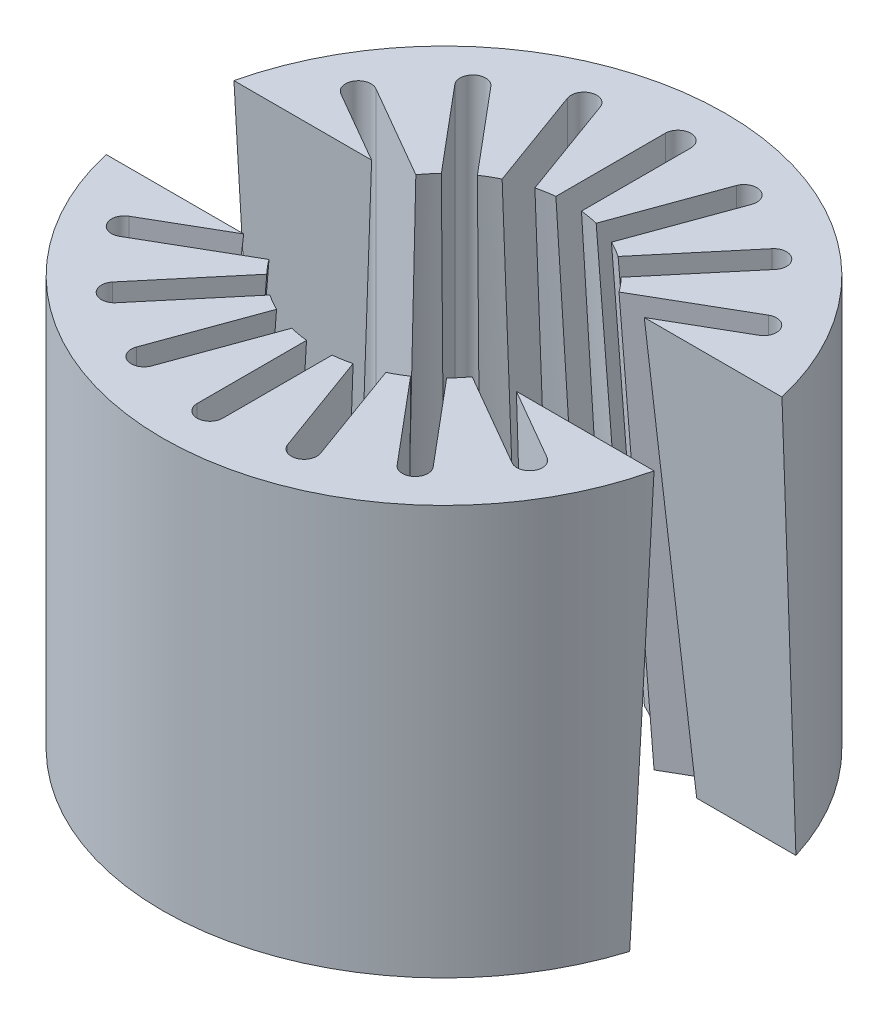
SolidWorks part; units mm, degrees
ref_plane "Front Plane" through (0, 0, 0) normal (0, 0, 1) x (1, 0, 0)
ref_plane "Top Plane" through (0, 0, 0) normal (0, 1, 0) x (1, 0, 0)
ref_plane "Right Plane" through (0, 0, 0) normal (1, 0, 0) x (0, 0, -1)
sketch "Sketch1" plane through (0, 0, 0) normal (0, 1, 0) x (1, 0, 0)
  line L1 (11, -7.5) -> (-11, -7.5) construction
  line L2 (11, -7.5) -> (11, 7.5) construction
  line L3 (11, 7.5) -> (-11, 7.5) construction
  line L4 (-11, -7.5) -> (-11, 7.5) construction
  line L5 (11, -7.5) -> (-11, 7.5) construction
  line L6 (11, 7.5) -> (-11, -7.5) construction
  circle A0 centre (0, 0) radius 5 construction
  circle A1 centre (0, 0) radius 11
  point P0 (0, 0)
  dimension "D1" = 10
  dimension "D2" = 22
  dimension "D3" = 15
extrude "Boss-Extrude1" add sketch "Sketch1" along normal blind 16
sketch "Sketch2" plane through (0, 0, 0) normal (1, 0, 0) x (0, 0, -1)
  line L0 (0, 0) -> (0, 16)
  line L2 (0, 16) -> (4.9, 16)
  line L3 (4.9, 16) -> (5.9, 0)
  line L5 (5.9, 0) -> (0, 0)
  line L6 (11, 16) -> (-11, 16) construction
  line L7 (-11, 0) -> (11, 0) construction
  dimension "D1" = 4.9
  dimension "5.9" = 5.9
revolve "Cut-Revolve1" cut sketch "Sketch2" angle 360 about L0
sketch "Sketch3" plane through (0, 16, 0) normal (0, 1, 0) x (1, 0, 0)
  line L0 (0, 4.8) -> (0, 0) construction
  line L1 (-0.5, 4.8) -> (0.5, 4.8)
  line L2 (-0.5, 4.8) -> (-0.5, 9.15)
  line L4 (0.5, 4.8) -> (0.5, 9.15)
  line L5 (1.1719, 4.6815) -> (2.1115, 4.3395)
  line L6 (1.1719, 4.6815) -> (2.6596, 8.7692)
  line L7 (2.1115, 4.3395) -> (3.5993, 8.4272)
  line L8 (2.7024, 3.9984) -> (3.4684, 3.3556)
  line L9 (2.7024, 3.9984) -> (5.4985, 7.3307)
  line L10 (3.4684, 3.3556) -> (6.2645, 6.6879)
  line L11 (3.9069, 2.833) -> (4.4069, 1.967)
  line L12 (3.9069, 2.833) -> (7.6741, 5.008)
  line L13 (4.4069, 1.967) -> (8.1741, 4.142)
  line L14 (4.6403, 1.3259) -> (4.8139, 0.3411)
  line L15 (4.6403, 1.3259) -> (8.9242, 2.0813)
  line L16 (4.8139, 0.3411) -> (9.0978, 1.0965)
  line L17 (4.8139, -0.3411) -> (4.6403, -1.3259)
  line L18 (4.8139, -0.3411) -> (9.0978, -1.0965)
  line L19 (4.6403, -1.3259) -> (8.9242, -2.0813)
  line L20 (4.4069, -1.967) -> (3.9069, -2.833)
  line L21 (4.4069, -1.967) -> (8.1741, -4.142)
  line L22 (3.9069, -2.833) -> (7.6741, -5.008)
  line L23 (3.4684, -3.3556) -> (2.7024, -3.9984)
  line L24 (3.4684, -3.3556) -> (6.2645, -6.6879)
  line L25 (2.7024, -3.9984) -> (5.4985, -7.3307)
  line L26 (2.1115, -4.3395) -> (1.1719, -4.6815)
  line L27 (2.1115, -4.3395) -> (3.5993, -8.4272)
  line L28 (1.1719, -4.6815) -> (2.6596, -8.7692)
  line L29 (0.5, -4.8) -> (-0.5, -4.8)
  line L30 (0.5, -4.8) -> (0.5, -9.15)
  line L31 (-0.5, -4.8) -> (-0.5, -9.15)
  line L32 (-1.1719, -4.6815) -> (-2.1115, -4.3395)
  line L33 (-1.1719, -4.6815) -> (-2.6596, -8.7692)
  line L34 (-2.1115, -4.3395) -> (-3.5993, -8.4272)
  line L35 (-2.7024, -3.9984) -> (-3.4684, -3.3556)
  line L36 (-2.7024, -3.9984) -> (-5.4985, -7.3307)
  line L37 (-3.4684, -3.3556) -> (-6.2645, -6.6879)
  line L38 (-3.9069, -2.833) -> (-4.4069, -1.967)
  line L39 (-3.9069, -2.833) -> (-7.6741, -5.008)
  line L40 (-4.4069, -1.967) -> (-8.1741, -4.142)
  line L41 (-4.6403, -1.3259) -> (-4.8139, -0.3411)
  line L42 (-4.6403, -1.3259) -> (-8.9242, -2.0813)
  line L43 (-4.8139, -0.3411) -> (-9.0978, -1.0965)
  line L44 (-4.8139, 0.3411) -> (-4.6403, 1.3259)
  line L45 (-4.8139, 0.3411) -> (-9.0978, 1.0965)
  line L46 (-4.6403, 1.3259) -> (-8.9242, 2.0813)
  line L47 (-4.4069, 1.967) -> (-3.9069, 2.833)
  line L48 (-4.4069, 1.967) -> (-8.1741, 4.142)
  line L49 (-3.9069, 2.833) -> (-7.6741, 5.008)
  line L50 (-3.4684, 3.3556) -> (-2.7024, 3.9984)
  line L51 (-3.4684, 3.3556) -> (-6.2645, 6.6879)
  line L52 (-2.7024, 3.9984) -> (-5.4985, 7.3307)
  line L53 (-2.1115, 4.3395) -> (-1.1719, 4.6815)
  line L54 (-2.1115, 4.3395) -> (-3.5993, 8.4272)
  line L55 (-1.1719, 4.6815) -> (-2.6596, 8.7692)
  arc A0 (0, 9.65) -> (0.5, 9.15) centre (0, 9.15) cw
  arc A1 (-0.5, 9.15) -> (0, 9.65) centre (0, 9.15) cw
  arc A2 (3.3005, 9.068) -> (3.5993, 8.4272) centre (3.1295, 8.5982) cw
  arc A3 (2.6596, 8.7692) -> (3.3005, 9.068) centre (3.1295, 8.5982) cw
  arc A4 (6.2029, 7.3923) -> (6.2645, 6.6879) centre (5.8815, 7.0093) cw
  arc A5 (5.4985, 7.3307) -> (6.2029, 7.3923) centre (5.8815, 7.0093) cw
  arc A6 (8.3571, 4.825) -> (8.1741, 4.142) centre (7.9241, 4.575) cw
  arc A7 (7.6741, 5.008) -> (8.3571, 4.825) centre (7.9241, 4.575) cw
  arc A8 (9.5034, 1.6757) -> (9.0978, 1.0965) centre (9.011, 1.5889) cw
  arc A9 (8.9242, 2.0813) -> (9.5034, 1.6757) centre (9.011, 1.5889) cw
  arc A10 (9.5034, -1.6757) -> (8.9242, -2.0813) centre (9.011, -1.5889) cw
  arc A11 (9.0978, -1.0965) -> (9.5034, -1.6757) centre (9.011, -1.5889) cw
  arc A12 (8.3571, -4.825) -> (7.6741, -5.008) centre (7.9241, -4.575) cw
  arc A13 (8.1741, -4.142) -> (8.3571, -4.825) centre (7.9241, -4.575) cw
  arc A14 (6.2029, -7.3923) -> (5.4985, -7.3307) centre (5.8815, -7.0093) cw
  arc A15 (6.2645, -6.6879) -> (6.2029, -7.3923) centre (5.8815, -7.0093) cw
  arc A16 (3.3005, -9.068) -> (2.6596, -8.7692) centre (3.1295, -8.5982) cw
  arc A17 (3.5993, -8.4272) -> (3.3005, -9.068) centre (3.1295, -8.5982) cw
  arc A18 (0, -9.65) -> (-0.5, -9.15) centre (0, -9.15) cw
  arc A19 (0.5, -9.15) -> (0, -9.65) centre (0, -9.15) cw
  arc A20 (-3.3005, -9.068) -> (-3.5993, -8.4272) centre (-3.1295, -8.5982) cw
  arc A21 (-2.6596, -8.7692) -> (-3.3005, -9.068) centre (-3.1295, -8.5982) cw
  arc A22 (-6.2029, -7.3923) -> (-6.2645, -6.6879) centre (-5.8815, -7.0093) cw
  arc A23 (-5.4985, -7.3307) -> (-6.2029, -7.3923) centre (-5.8815, -7.0093) cw
  arc A24 (-8.3571, -4.825) -> (-8.1741, -4.142) centre (-7.9241, -4.575) cw
  arc A25 (-7.6741, -5.008) -> (-8.3571, -4.825) centre (-7.9241, -4.575) cw
  arc A26 (-9.5034, -1.6757) -> (-9.0978, -1.0965) centre (-9.011, -1.5889) cw
  arc A27 (-8.9242, -2.0813) -> (-9.5034, -1.6757) centre (-9.011, -1.5889) cw
  arc A28 (-9.5034, 1.6757) -> (-8.9242, 2.0813) centre (-9.011, 1.5889) cw
  arc A29 (-9.0978, 1.0965) -> (-9.5034, 1.6757) centre (-9.011, 1.5889) cw
  arc A30 (-8.3571, 4.825) -> (-7.6741, 5.008) centre (-7.9241, 4.575) cw
  arc A31 (-8.1741, 4.142) -> (-8.3571, 4.825) centre (-7.9241, 4.575) cw
  arc A32 (-6.2029, 7.3923) -> (-5.4985, 7.3307) centre (-5.8815, 7.0093) cw
  arc A33 (-6.2645, 6.6879) -> (-6.2029, 7.3923) centre (-5.8815, 7.0093) cw
  arc A34 (-3.3005, 9.068) -> (-2.6596, 8.7692) centre (-3.1295, 8.5982) cw
  arc A35 (-3.5993, 8.4272) -> (-3.3005, 9.068) centre (-3.1295, 8.5982) cw
  point P131 (0, 0)
  dimension "D1" = 0.5
  dimension "D2" = 4.35
  dimension "D3" = 4.8
  dimension "D4" = 1
  dimension "D5" = 18
extrude "Cut-Extrude1" cut sketch "Sketch3" against normal through all
sketch "Sketch4" plane through (0, 0, 0) normal (1, 0, 0) x (0, 0, -1)
  line L0 (0, 16) -> (0, 0) construction
  line L1 (11, 16) -> (-11, 16) construction
  line L2 (0, 16) -> (2.5, 16)
  line L3 (2.5, 16) -> (3.25, 0)
  line L4 (-11, 0) -> (11, 0) construction
  line L5 (3.25, 0) -> (-3.25, 0)
  line L6 (-3.25, 0) -> (-2.5, 16)
  line L7 (-2.5, 16) -> (0, 16)
  dimension "D1" = 5
  dimension "D2" = 6.5
extrude "Cut-Extrude2" cut sketch "Sketch4" against normal mid plane 30
